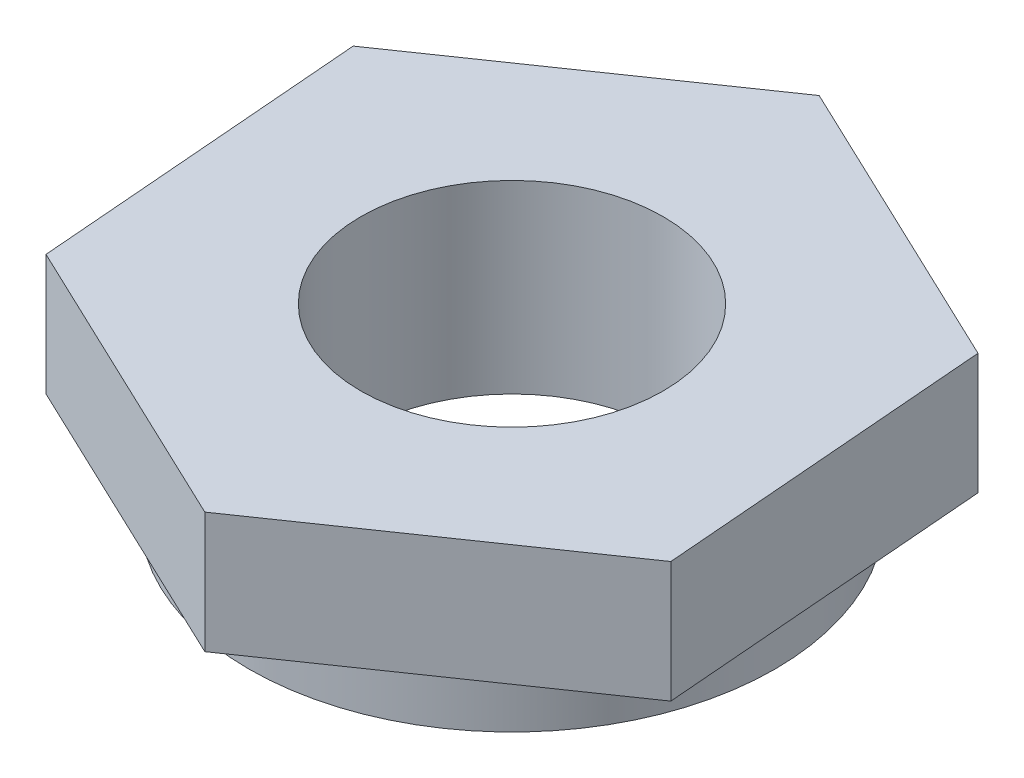
SolidWorks part; units mm, degrees
ref_plane "前视基准面" through (0, 0, 0) normal (0, 0, 1) x (1, 0, 0)
ref_plane "上视基准面" through (0, 0, 0) normal (0, 1, 0) x (1, 0, 0)
ref_plane "右视基准面" through (0, 0, 0) normal (1, 0, 0) x (0, 0, -1)
sketch "草图1" plane through (0, 0, 0) normal (0, 1, 0) x (1, 0, 0)
  line L1 (2.5031, -1.1893) -> (2.2815, 1.5731)
  line L2 (2.2815, 1.5731) -> (-0.2216, 2.7624)
  line L3 (-0.2216, 2.7624) -> (-2.5031, 1.1893)
  line L4 (-2.5031, 1.1893) -> (-2.2815, -1.5731)
  line L5 (-2.2815, -1.5731) -> (0.2216, -2.7624)
  line L6 (0.2216, -2.7624) -> (2.5031, -1.1893)
  circle A0 centre (0, 0) radius 2.4 construction
  dimension "D1" = 4.8
extrude "凸台-拉伸1" add sketch "草图1" along normal blind 1
sketch "草图2" plane through (0, 0, 0) normal (0, -1, 0) x (1, 0, 0)
  circle A0 centre (0, 0) radius 2.175
extrude "凸台-拉伸2" add sketch "草图2" along normal blind 0.53 contours A0
sketch "草图3" plane through (0, -0.53, 0) normal (0, -1, 0) x (-1, 0, 0)
  circle A0 centre (0, 0) radius 1.25
  dimension "D1" = 2.5
extrude "切除-拉伸1" cut sketch "草图3" against normal through all
